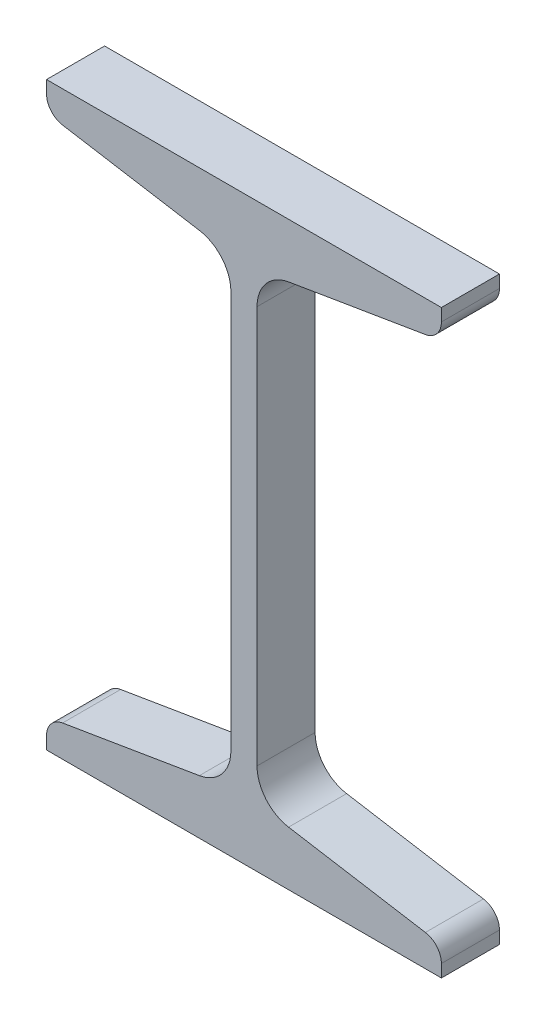
SolidWorks part; units mm, degrees
material "普通碳钢"
ref_plane "前视基准面" through (0, 0, 0) normal (0, 0, 1) x (1, 0, 0)
ref_plane "上视基准面" through (0, 0, 0) normal (0, 1, 0) x (1, 0, 0)
ref_plane "右视基准面" through (0, 0, 0) normal (1, 0, 0) x (0, 0, -1)
sketch "草图1" plane through (0, 0, 0) normal (0, 0, 1) x (1, 0, 0)
  line L0 (0, 57.7936) -> (0, -50.1257) construction
  line L1 (-61.0596, 0) -> (51.9716, 0) construction
  line L2 (34, 50) -> (-34, 50)
  line L3 (-34, 50) -> (-34, 45.0458)
  line L4 (-34, 45.0458) -> (-2.25, 39.7542)
  line L5 (-2.25, 39.7542) -> (-2.25, -39.7542)
  line L6 (2.25, 39.7542) -> (2.25, -39.7542)
  line L7 (34, 45.0458) -> (2.25, 39.7542)
  line L8 (34, 50) -> (34, 45.0458)
  line L9 (34, -50) -> (-34, -50)
  line L10 (-34, -45.0458) -> (-2.25, -39.7542)
  line L11 (-34, -50) -> (-34, -45.0458)
  line L12 (34, -50) -> (34, -45.0458)
  line L13 (34, -45.0458) -> (2.25, -39.7542)
  line L14 (18.125, 42.4) -> (18.125, 50) construction
  point P14 (0, 50)
  point P17 (0, -50)
  point P22 (0, 0)
  dimension "D1" = 100
  dimension "D2" = 68
  dimension "D3" = 4.5
  dimension "D4" = 7.6
  dimension "D5" = 9.462
extrude "凸台-拉伸1" add sketch "草图1" along normal blind 10
fillet "圆角1" radius 3.3 4 edges at (34, -45.0458, 5) (-34, -45.0458, 5) (-34, 45.0458, 5) (34, 45.0458, 5)
fillet "圆角2" radius 6.5 4 edges at (-2.25, -39.7542, 5) (-2.25, 39.7542, 5) (2.25, -39.7542, 5) (2.25, 39.7542, 5)
